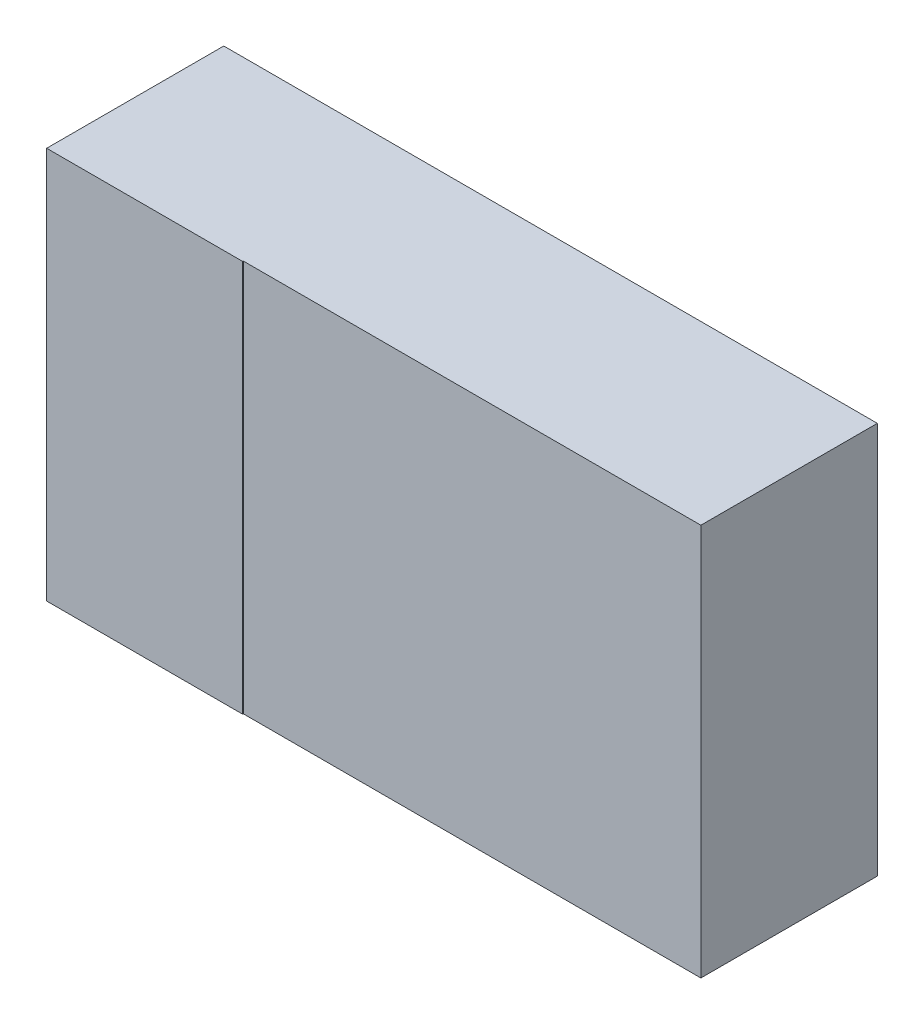
SolidWorks part; units mm, degrees
ref_plane "Plan de face" through (0, 0, 0) normal (0, 0, 1) x (1, 0, 0)
ref_plane "Plan de dessus" through (0, 0, 0) normal (0, 1, 0) x (1, 0, 0)
ref_plane "Plan de droite" through (0, 0, 0) normal (1, 0, 0) x (0, 0, -1)
sketch "Esquisse1" plane through (0, 0, 0) normal (0, 0, 1) x (1, 0, 0)
  line L0 (0, 0.25) -> (0, -0.25) construction
  line L1 (-0.45, 0.25) -> (-0.2, 0.25)
  line L2 (-0.45, 0.25) -> (-0.45, -0.25)
  line L3 (-0.45, -0.25) -> (-0.2, -0.25)
  line L4 (-0.2, 0.25) -> (-0.2, -0.25)
  line L5 (-0.45, 0.25) -> (-0.2, -0.25) construction
  line L6 (-0.45, -0.25) -> (-0.2, 0.25) construction
  line L7 (0.45, 0.25) -> (0.2, 0.25)
  line L8 (0.45, 0.25) -> (0.45, -0.25)
  line L9 (0.45, -0.25) -> (0.2, -0.25)
  line L10 (0.2, 0.25) -> (0.2, -0.25)
  point P0 (-0.325, 0)
  dimension "D1" = 0.25
  dimension "D2" = 0.5
  dimension "D3" = 0.65
extrude "pads" add sketch "Esquisse1" along normal blind 0.03
sketch "Esquisse2" plane through (0, 0, 0.03) normal (0, 0, 1) x (1, 0, 0)
  line L1 (0.5, 0.3) -> (-0.5, 0.3)
  line L2 (0.5, 0.3) -> (0.5, -0.3)
  line L3 (0.5, -0.3) -> (-0.5, -0.3)
  line L4 (-0.5, 0.3) -> (-0.5, -0.3)
  line L5 (0.5, 0.3) -> (-0.5, -0.3) construction
  line L6 (0.5, -0.3) -> (-0.5, 0.3) construction
  point P0 (0, 0)
  dimension "D1" = 1
  dimension "D2" = 0.6
extrude "body" add sketch "Esquisse2" along normal blind 0.27
sketch "Esquisse3" plane through (0, 0, 0.3) normal (0, 0, 1) x (1, 0, 0)
  line L0 (-0.5, -0.3) -> (0.5, -0.3) construction
  line L1 (-0.5, 0.3) -> (-0.2, 0.3)
  line L2 (-0.5, 0.3) -> (-0.5, -0.3)
  line L3 (-0.5, -0.3) -> (-0.2, -0.3)
  line L4 (-0.2, 0.3) -> (-0.2, -0.3)
  point P7 (-0.0902, 0.3)
  dimension "D1" = 0.3
extrude "mark" add sketch "Esquisse3" along normal blind 0.001
